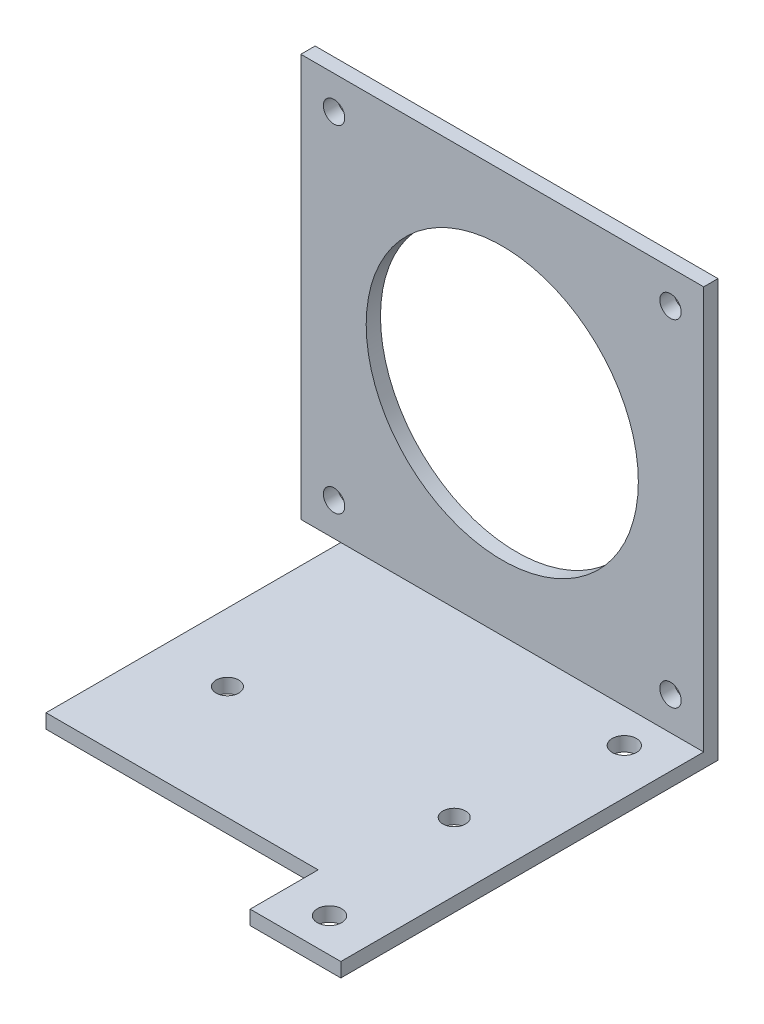
SolidWorks part; units mm, degrees
material "Galvanized Steel"
ref_plane "Front Plane" through (0, 0, 0) normal (0, 0, 1) x (1, 0, 0)
ref_plane "Top Plane" through (0, 0, 0) normal (0, 1, 0) x (1, 0, 0)
ref_plane "Right Plane" through (0, 0, 0) normal (1, 0, 0) x (0, 0, -1)
sketch "Sketch1" plane through (0, 0, 0) normal (0, 1, 0) x (1, 0, 0)
  line L0 (9.525, 15.875) -> (41.275, 15.875) construction
  line L2 (0, 43.275) -> (50.8, 43.275)
  line L3 (50.8, 43.275) -> (50.8, -9.525)
  line L4 (50.8, -9.525) -> (38.1, -9.525)
  line L5 (38.1, -9.525) -> (38.1, 0)
  line L6 (38.1, 0) -> (0, 0)
  line L7 (0, 0) -> (0, 43.275)
  line L8 (44.45, 36.5125) -> (44.45, -4.7625) construction
  circle A0 centre (44.45, 36.5125) radius 1.7
  circle A1 centre (44.45, -4.7625) radius 1.7
  circle A2 centre (9.525, 15.875) radius 1.5875
  circle A3 centre (41.275, 15.875) radius 1.5875
  dimension "D5" = 3.4
  dimension "D9" = 3.175
  dimension "D4" = 9.525
  dimension "D1" = 50.8
  dimension "D2" = 52.8
  dimension "D3" = 12.7
  dimension "D6" = 41.275
  dimension "D7" = 6.35
  dimension "D8" = 25.4
  dimension "D10" = 31.75
  dimension "D11" = 9.525
  dimension "D12" = 4.7625
extrude "Boss-Extrude1" add sketch "Sketch1" along normal blind 2
sketch "Sketch2" plane through (0, 2, 0) normal (0, 1, 0) x (1, 0, 0)
  line L0 (50.8, 43.275) -> (50.8, 41.275)
  line L2 (50.8, -9.525) -> (50.8, 43.275) construction
  line L3 (50.8, 41.275) -> (-5.6, 41.275)
  line L5 (-5.6, 41.275) -> (-5.6, 43.275)
  line L6 (-5.6, 43.275) -> (50.8, 43.275)
  dimension "D1" = 56.4
  dimension "D2" = 2
extrude "Boss-Extrude2" add sketch "Sketch2" along normal blind 56.4
sketch "Sketch3" plane through (0, 0, -43.275) normal (0, 0, -1) x (-1, 0, 0)
  line L0 (-50.8, 58.4) -> (5.6, 2) construction
  line L1 (5.6, 58.4) -> (-50.8, 2) construction
  line L2 (-50.8, 58.4) -> (-50.8, 0) construction
  circle A0 centre (-22.6, 30.2) radius 19.05
  circle A1 centre (0.95, 53.75) radius 1.5
  circle A2 centre (0.95, 6.65) radius 1.5
  circle A3 centre (-46.15, 6.65) radius 1.5
  circle A4 centre (-46.15, 53.75) radius 1.5
  dimension "D1" = 3
  dimension "D3" = 38.1
  dimension "D2" = 47.1
extrude "Cut-Extrude1" cut sketch "Sketch3" against normal through all
